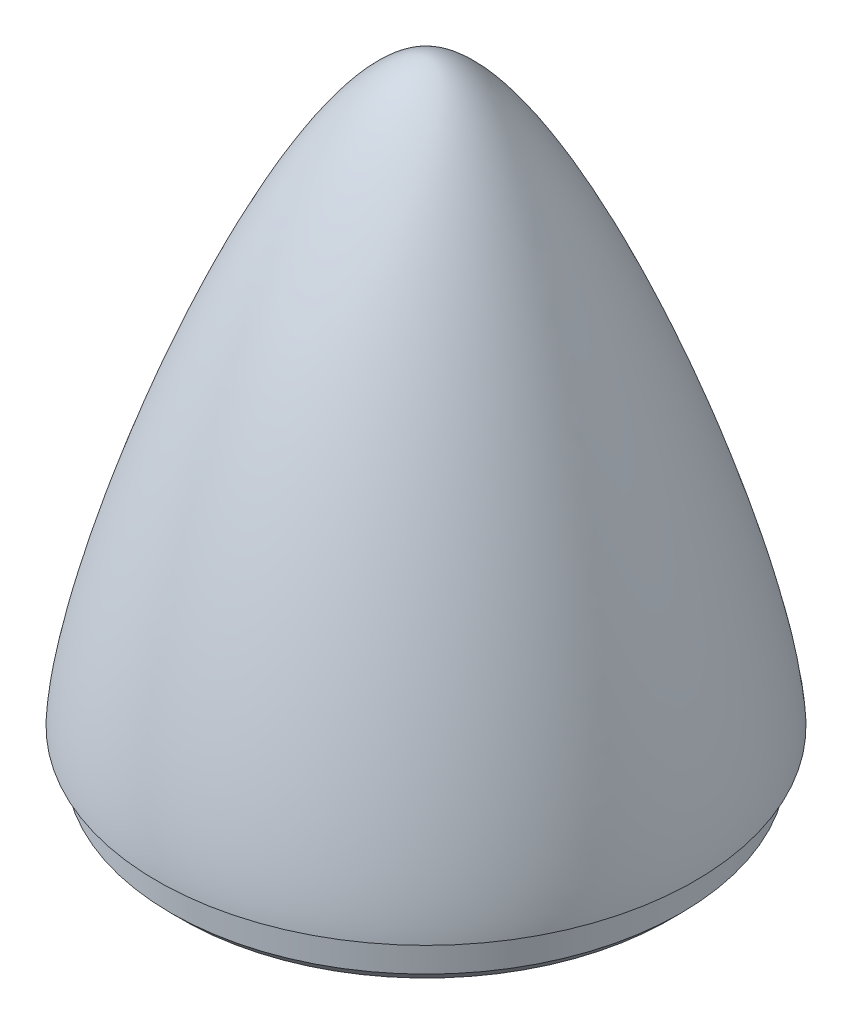
SolidWorks part; units mm, degrees
ref_plane "Front Plane" through (0, 0, 0) normal (0, 0, 1) x (1, 0, 0)
ref_plane "Top Plane" through (0, 0, 0) normal (0, 1, 0) x (1, 0, 0)
ref_plane "Right Plane" through (0, 0, 0) normal (1, 0, 0) x (0, 0, -1)
sketch "Sketch2" plane through (0, 0, 0) normal (0, 0, 1) x (1, 0, 0)
  line L0 (0, 122.2821) -> (0, 181.6557) construction
  line L2 (0, 118.2821) -> (-21, 118.2821)
  line L4 (-22, 119.2821) -> (-22, 122.2821)
  line L5 (-22, 122.2821) -> (-23.2, 122.2821)
  line L6 (0, 118.2821) -> (0, 172.2821)
  line L8 (-23.2, 122.2821) -> (-22.6744, 133.2282) construction
  line L9 (-22.6744, 133.2282) -> (-8.9137, 172.1145) construction
  line L10 (-8.9137, 172.1145) -> (0, 172.2821) construction
  line L11 (-21, 118.2821) -> (-22, 119.2821)
  spline S0 degree 3 poles (-23.2, 122.2821) (-22.6744, 133.2282) (-8.9137, 172.1145) (0, 172.2821) knots 0 0 0 0 1 1 1 1
  point P6 (-22, 118.2821)
  dimension "D1" = 4
  dimension "D2" = 50
  dimension "D3" = 1.2
  dimension "D4" = 22
revolve "Revolve3" add sketch "Sketch2" angle 360 about L0
